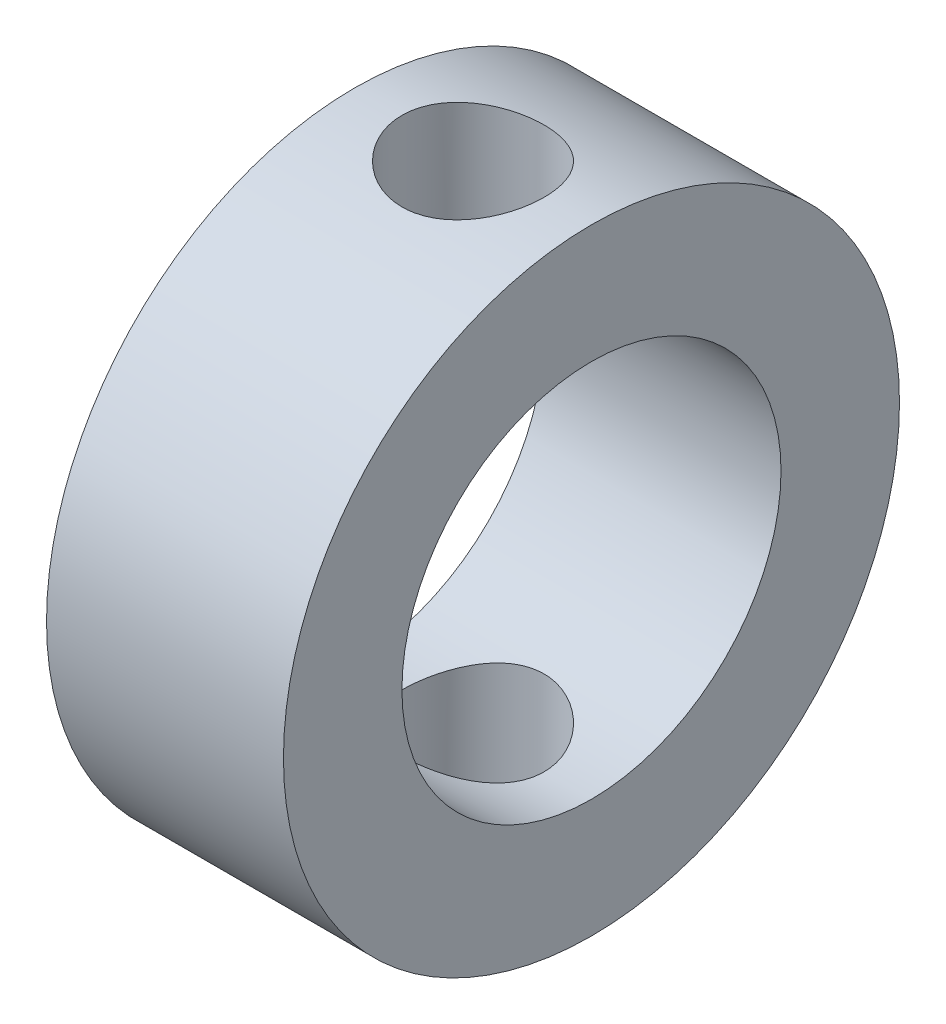
SolidWorks part; units mm, degrees
ref_plane "Front Plane" through (0, 0, 0) normal (1, 0, 0) x (0, 1, 0)
ref_plane "Top Plane" through (0, 0, 0) normal (0, 0, 1) x (0, 1, 0)
ref_plane "Right Plane" through (0, 0, 0) normal (0, 1, 0) x (-1, 0, 0)
sketch "Sketch1" plane through (0, 0, 0) normal (1, 0, 0) x (0, 1, 0)
  circle A0 centre (0, 0) radius 8
  circle A1 centre (0, 0) radius 13
  dimension "D1" = 16
  dimension "D2" = 26
extrude "Boss-Extrude1" add sketch "Sketch1" along normal mid plane 10
sketch "Sketch2" plane through (0, 0, 0) normal (0, 1, 0) x (-1, 0, 0)
  circle A0 centre (0, 0) radius 3
  dimension "D1" = 6
extrude "Cut-Extrude1" cut sketch "Sketch2" against normal through all both and the other way through all
